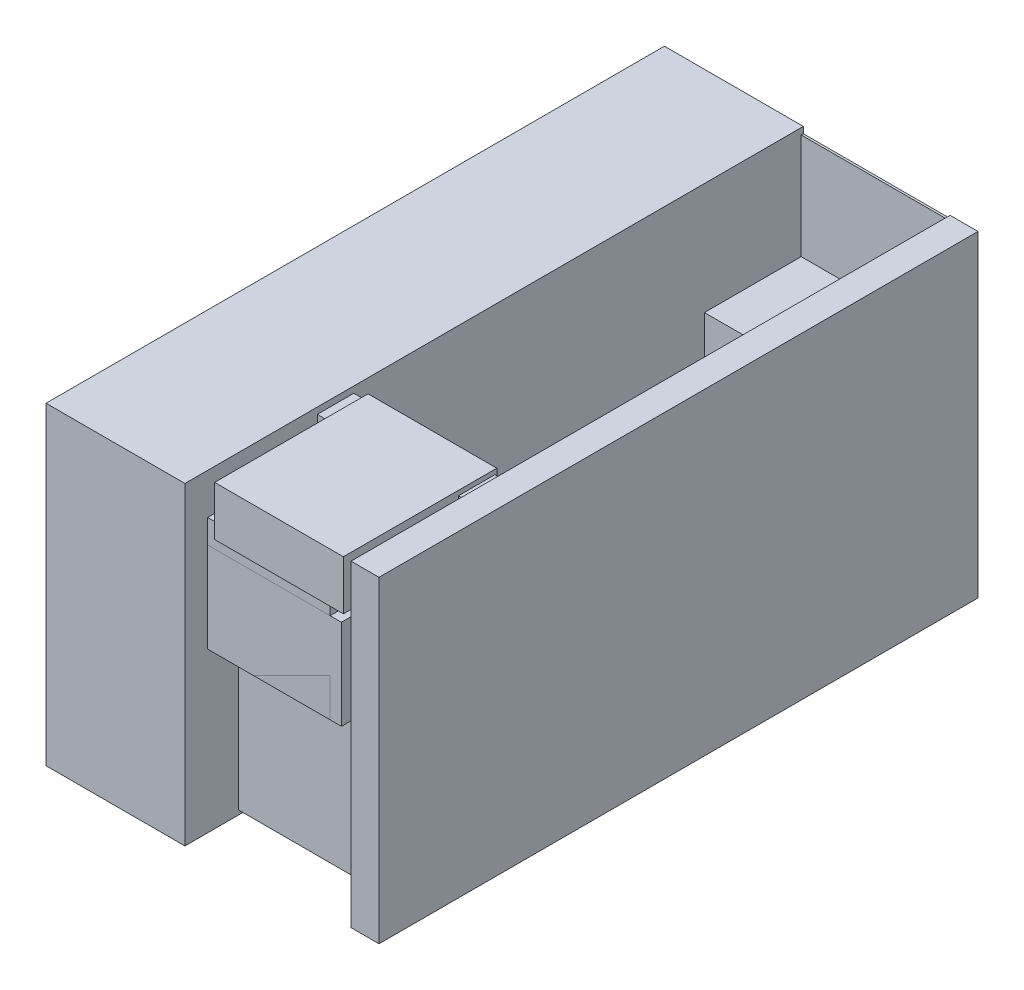
SolidWorks part; units mm, degrees
other "COLL.BOX-Estrusione-Estrusione12"
other "COLL.BOX-Estrusione-Estrusione11"
other "COLL.BOX-Estrusione-Estrusione9"
other "COLL.BOX-Estrusione-Estrusione7"
other "COLL.BOX-Estrusione-Estrusione6"
other "COLL.BOX-Estrusione-Estrusione5"
ref_plane "Piano frontale" through (0, 0, 0) normal (0, 0, 1) x (1, 0, 0)
ref_plane "Piano superiore" through (0, 0, 0) normal (0, 1, 0) x (1, 0, 0)
ref_plane "Piano destro" through (0, 0, 0) normal (1, 0, 0) x (0, 0, -1)
sketch "Schizzo1" plane through (0, 0, 0) normal (0, 0, 1) x (1, 0, 0)
  line L1 (-350, 350) -> (350, 350)
  line L2 (-350, 350) -> (-350, -350)
  line L3 (-350, -350) -> (350, -350)
  line L4 (350, 350) -> (350, -350)
  line L5 (-350, 350) -> (350, -350) construction
  line L6 (-350, -350) -> (350, 350) construction
  point P0 (0, 0)
  dimension "D1" = 700
  dimension "D2" = 700
extrude "Estrusione-Estrusione1" add sketch "Schizzo1" along normal blind 1130
sketch "Schizzo2" plane through (0, 0, 1130) normal (0, 0, 1) x (1, 0, 0)
  line L0 (350, -350) -> (350, 350) construction
  line L1 (-90, 270) -> (240, 270)
  line L2 (-90, 270) -> (-90, 5)
  line L3 (-90, 5) -> (240, 5)
  line L4 (240, 270) -> (240, 5)
  line L5 (-90, 270) -> (240, 5) construction
  line L6 (-90, 5) -> (240, 270) construction
  line L7 (-350, 350) -> (-350, -350) construction
  line L9 (-350, -350) -> (350, -350) construction
  point P0 (75, 137.5)
  dimension "D1" = 110
  dimension "D2" = 260
  dimension "D3" = 265
  dimension "D4" = 355
extrude "Estrusione-Estrusione2" add sketch "Schizzo2" along normal blind 255 separate body
sketch "Schizzo3" plane through (0, 0, 1130) normal (0, 0, 1) x (1, 0, 0)
  line L0 (-350, 350) -> (-350, -350) construction
  line L1 (-90, 195) -> (-240, 195)
  line L2 (-90, 195) -> (-90, 100)
  line L3 (-90, 100) -> (-240, 100)
  line L4 (-240, 195) -> (-240, 100)
  line L5 (-90, 195) -> (-240, 100) construction
  line L6 (-90, 100) -> (-240, 195) construction
  line L7 (-90, 5) -> (240, 5) construction
  point P0 (-165, 147.5)
  dimension "D1" = 150
  dimension "D2" = 110
  dimension "D3" = 95
  dimension "D4" = 95
extrude "Estrusione-Estrusione3" add sketch "Schizzo3" along normal blind 210 separate body
sketch "Schizzo5" plane through (0, 350, 0) normal (0, 1, 0) x (1, 0, 0)
  line L0 (350, 0) -> (-350, 0) construction
  line L1 (300, -1045) -> (-50, -1045)
  line L2 (300, -1045) -> (300, -5)
  line L3 (300, -5) -> (-50, -5)
  line L4 (-50, -1045) -> (-50, -5)
  line L5 (300, -1045) -> (-50, -5) construction
  line L6 (300, -5) -> (-50, -1045) construction
  line L7 (350, -1130) -> (350, 0) construction
  point P0 (125, -525)
  point P5 (153.4813, -606.9758)
  point P8 (140.0254, -525)
  dimension "D1" = 5
  dimension "D2" = 1040
  dimension "D3" = 350
  dimension "D4" = 50
extrude "Taglio-Estrusione1" cut sketch "Schizzo5" against normal blind 245
sketch "Schizzo7" plane through (0, 105, 0) normal (0, 1, 0) x (1, 0, 0)
  line L0 (300, -1045) -> (300, -5) construction
  line L1 (300, -230) -> (-50, -230)
  line L2 (300, -230) -> (300, -695)
  line L3 (300, -695) -> (-50, -695)
  line L4 (-50, -230) -> (-50, -695)
  line L5 (-50, -5) -> (-50, -1045) construction
  line L6 (300, -5) -> (-50, -5) construction
  dimension "D1" = 225
  dimension "D2" = 465
extrude "Taglio-Estrusione2" cut sketch "Schizzo7" against normal blind 95
sketch "Schizzo8" plane through (0, 105, 0) normal (0, 1, 0) x (1, 0, 0)
  line L1 (300, -695) -> (-50, -695)
  line L2 (300, -695) -> (300, -1045)
  line L3 (300, -1045) -> (-50, -1045)
  line L4 (-50, -695) -> (-50, -1045)
extrude "Taglio-Estrusione3" cut sketch "Schizzo8" against normal blind 458
sketch "Schizzo9" plane through (0, 0, 1045) normal (0, 0, -1) x (-1, 0, 0)
  line L0 (-300, -350) -> (-300, 350) construction
  line L1 (-220, 250) -> (70, 250)
  line L2 (-220, 250) -> (-220, 25)
  line L3 (-220, 25) -> (70, 25)
  line L4 (70, 250) -> (70, 25)
  line L5 (50, 350) -> (-300, 350) construction
  point P8 (-125, 350)
  dimension "D1" = 80
  dimension "D2" = 100
  dimension "D3" = 290
  dimension "D4" = 225
extrude "Taglio-Estrusione5" cut sketch "Schizzo9" against normal blind 320
sketch "Schizzo10" plane through (-350, 0, 0) normal (-1, 0, 0) x (0, 0, 1)
  line L1 (0, 364.7344) -> (1437.6108, 364.7344)
  line L2 (0, 364.7344) -> (0, -365.1054)
  line L3 (0, -365.1054) -> (1437.6108, -365.1054)
  line L4 (1437.6108, 364.7344) -> (1437.6108, -365.1054)
extrude "Estrusione-Estrusione5" add sketch "Schizzo10" against normal blind 305 and the other way blind 18 separate body
sketch "Schizzo11" plane through (350, 0, 0) normal (1, 0, 0) x (0, 0, -1)
  line L1 (0, 356.267) -> (-1392.524, 356.267)
  line L2 (0, 356.267) -> (0, -381.6487)
  line L3 (0, -381.6487) -> (-1392.524, -381.6487)
  line L4 (-1392.524, 356.267) -> (-1392.524, -381.6487)
extrude "Estrusione-Estrusione6" add sketch "Schizzo11" against normal blind 54 and the other way blind 11 separate body
sketch "Schizzo12" plane through (0, 350, 0) normal (0, 1, 0) x (1, 0, 0)
  line L1 (-16.362, -1040.6561) -> (282.9877, -1040.6561)
  line L2 (-16.362, -1040.6561) -> (-16.362, -1397.305)
  line L3 (-16.362, -1397.305) -> (282.9877, -1397.305)
  line L4 (282.9877, -1040.6561) -> (282.9877, -1397.305)
extrude "Estrusione-Estrusione7" add sketch "Schizzo12" against normal blind 104 and the other way blind 11 separate body
sketch "Schizzo15" plane through (0, 0, 1385) normal (0, 0, 1) x (1, 0, 0)
  line L1 (266.1042, 5) -> (-45.8637, 5)
  line L2 (266.1042, 5) -> (266.1042, 214.5875)
  line L3 (266.1042, 214.5875) -> (-45.8637, 214.5875)
  line L4 (-45.8637, 5) -> (-45.8637, 214.5875)
extrude "Estrusione-Estrusione9" add sketch "Schizzo15" against normal blind 38 separate body
sketch "Schizzo18" plane through (0, 10, 0) normal (0, 1, 0) x (1, 0, 0)
  line L0 (300, -230) -> (-50, -230) construction
  line L1 (282.631, -230) -> (0, -230)
  line L2 (282.631, -230) -> (282.631, -709.9861)
  line L3 (282.631, -709.9861) -> (0, -709.9861)
  line L4 (0, -230) -> (0, -709.9861)
extrude "Estrusione-Estrusione11" add sketch "Schizzo18" against normal blind 375 separate body
sketch "Schizzo19" plane through (0, 0, 1045) normal (0, 0, -1) x (-1, 0, 0)
  line L1 (26.2483, 31.9752) -> (-253.5151, 31.9752)
  line L2 (26.2483, 31.9752) -> (26.2483, -335.9782)
  line L3 (26.2483, -335.9782) -> (-253.5151, -335.9782)
  line L4 (-253.5151, 31.9752) -> (-253.5151, -335.9782)
extrude "Estrusione-Estrusione12" add sketch "Schizzo19" against normal blind 287 separate body
